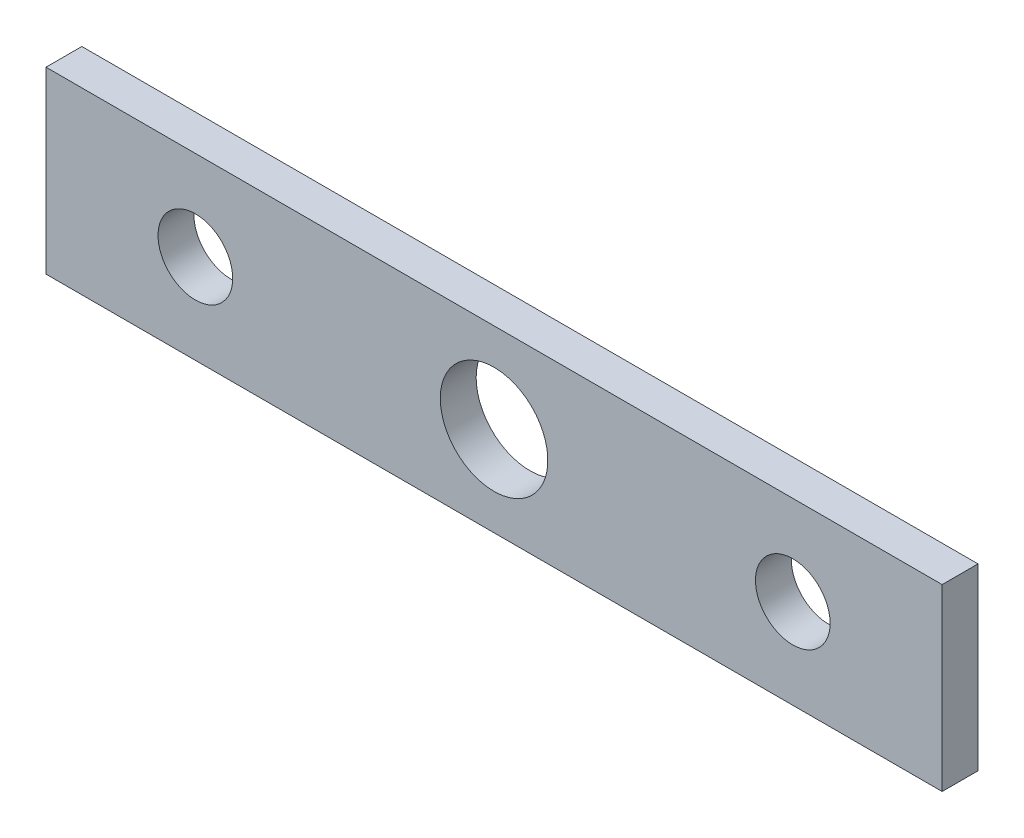
SolidWorks part; units mm, degrees
ref_plane "前视基准面" through (0, 0, 0) normal (0, 0, 1) x (1, 0, 0)
ref_plane "上视基准面" through (0, 0, 0) normal (0, 1, 0) x (1, 0, 0)
ref_plane "右视基准面" through (0, 0, 0) normal (1, 0, 0) x (0, 0, -1)
sketch "草图1" plane through (0, 0, 0) normal (0, 0, 1) x (1, 0, 0)
  line L0 (-100, 0) -> (100, 0) construction
  line L1 (-150, -30) -> (150, -30)
  line L2 (-150, -30) -> (-150, 30)
  line L3 (-150, 30) -> (150, 30)
  line L4 (150, -30) -> (150, 30)
  line L5 (-150, -30) -> (150, 30) construction
  line L6 (-150, 30) -> (150, -30) construction
  line L7 (0, 0) -> (0, -34.4476) construction
  circle A0 centre (100, 0) radius 12.5
  circle A1 centre (-100, 0) radius 12.5
  point P0 (0, 0)
  point P12 (0, 0)
  dimension "D5" = 25
  dimension "D6" = 25
  dimension "D1" = 300
  dimension "D2" = 60
  dimension "D3" = 200
extrude "凸台-拉伸1" add sketch "草图1" along normal blind 12
sketch "草图2" plane through (0, 0, 0) normal (0, 0, -1) x (-1, 0, 0)
  circle A0 centre (0, 0) radius 18
  dimension "D1" = 36
extrude "切除-拉伸1" cut sketch "草图2" against normal up to next
